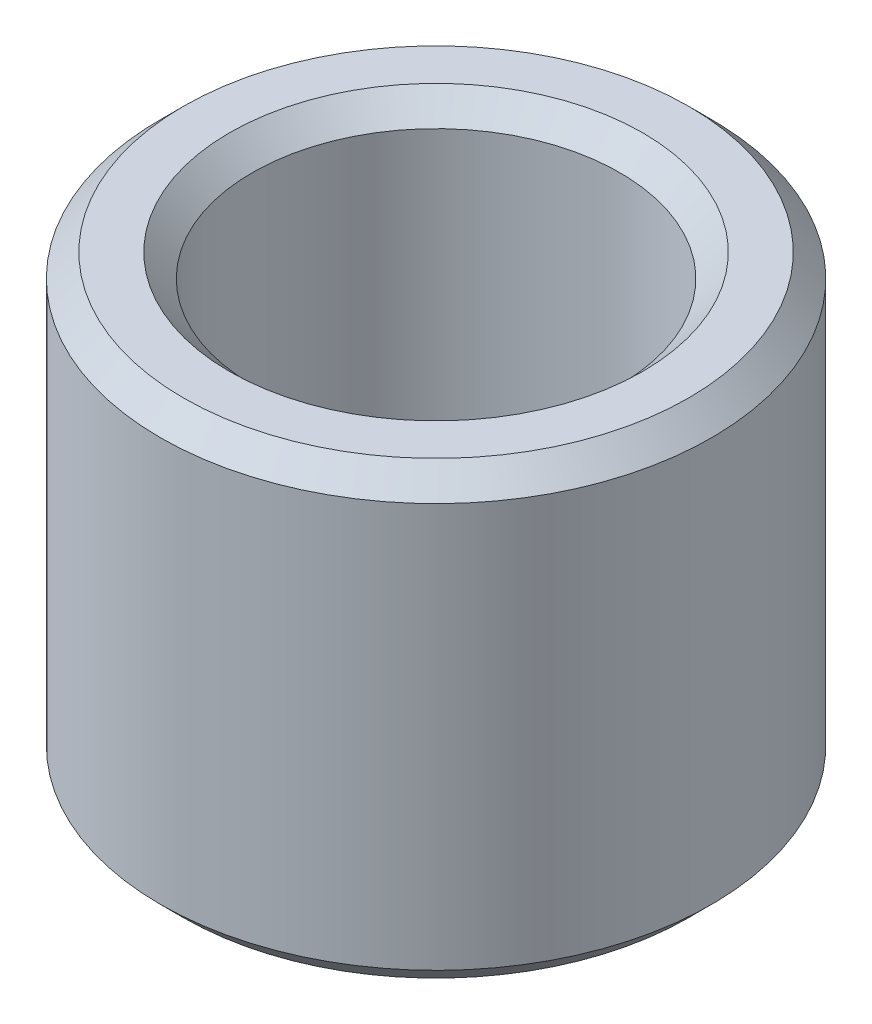
SolidWorks part; units mm, degrees
material "黄銅"
ref_plane "正面" through (0, 0, 0) normal (0, 0, 1) x (1, 0, 0)
ref_plane "平面" through (0, 0, 0) normal (0, 1, 0) x (1, 0, 0)
ref_plane "右側面" through (0, 0, 0) normal (1, 0, 0) x (0, 0, -1)
sketch "ｽｹｯﾁ1" plane through (0, 0, 0) normal (0, 1, 0) x (1, 0, 0)
  circle A0 centre (0, 0) radius 2
  circle A1 centre (0, 0) radius 3
  dimension "D1" = 4
  dimension "D2" = 6
extrude "ﾎﾞｽ - 押し出し1" add sketch "ｽｹｯﾁ1" along normal mid plane 4.9
chamfer "面取り1" distance 0.25 angle 45 4 edges at (0, -2.45, 3) (0, 2.45, 3) (0, -2.45, 2) (0, 2.45, 2)
